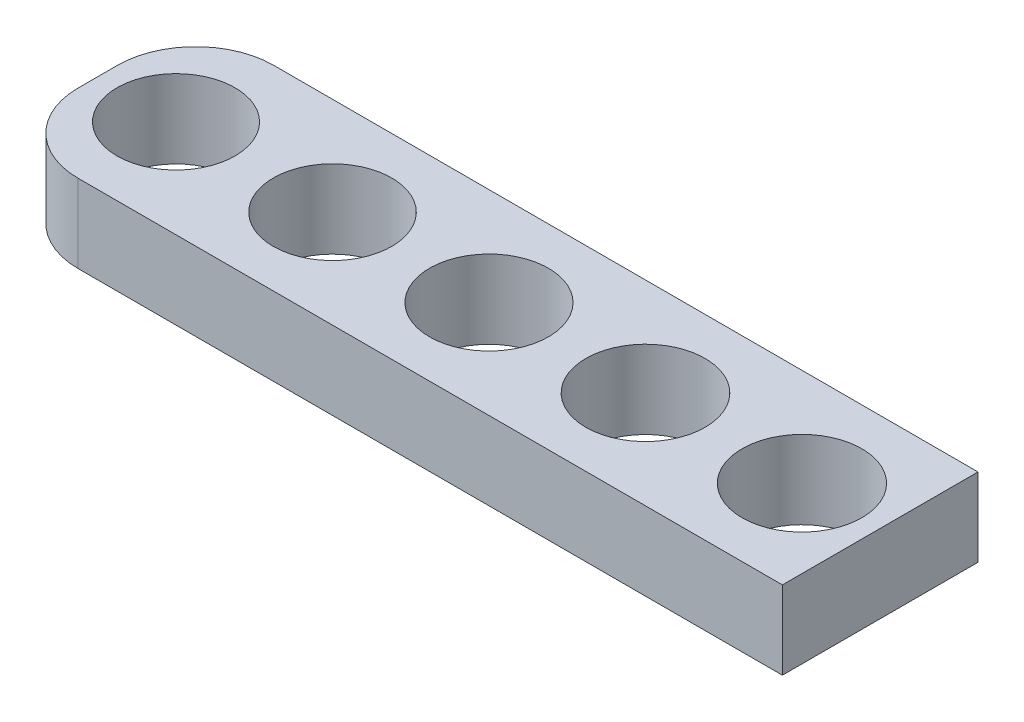
SolidWorks part; units mm, degrees
ref_plane "Front Plane" through (0, 0, 0) normal (0, 0, 1) x (1, 0, 0)
ref_plane "Top Plane" through (0, 0, 0) normal (0, 1, 0) x (1, 0, 0)
ref_plane "Right Plane" through (0, 0, 0) normal (1, 0, 0) x (0, 0, -1)
sketch "Sketch1" plane through (0, 0, 0) normal (0, 1, 0) x (1, 0, 0)
  line L0 (-40, 0) -> (-20, 0) construction
  line L1 (-40, 12.5) -> (50, 12.5)
  line L2 (-50, 2.5) -> (-50, -2.5)
  line L3 (-40, -12.5) -> (50, -12.5)
  line L4 (50, 12.5) -> (50, -12.5)
  line L5 (-50, 12.5) -> (50, -12.5) construction
  line L6 (-50, -12.5) -> (50, 12.5) construction
  line L7 (-20, 0) -> (0, 0) construction
  line L8 (0, 0) -> (20, 0) construction
  line L9 (20, 0) -> (40, 0) construction
  circle A0 centre (-40, 0) radius 7.55
  circle A1 centre (-20, 0) radius 7.575
  circle A2 centre (0, 0) radius 7.6
  circle A3 centre (20, 0) radius 7.625
  circle A4 centre (40, 0) radius 7.65
  arc A5 (-50, -2.5) -> (-40, -12.5) centre (-40, -2.5) ccw
  arc A6 (-40, 12.5) -> (-50, 2.5) centre (-40, 2.5) ccw
  point P0 (0, 0)
  dimension "D4" = 15.1
  dimension "D5" = 15.15
  dimension "D6" = 15.2
  dimension "D7" = 15.25
  dimension "D8" = 15.3
  dimension "D9" = 10
  dimension "D1" = 25
  dimension "D2" = 20
  dimension "D3" = 100
extrude "Boss-Extrude1" add sketch "Sketch1" along normal blind 10
